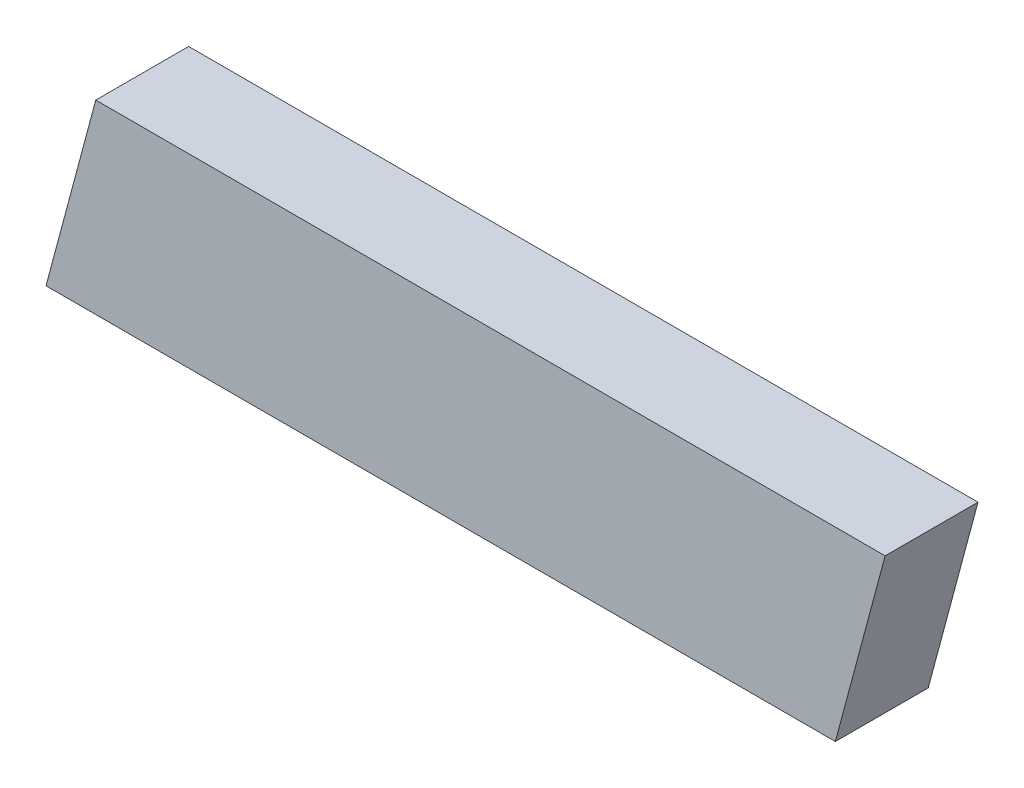
SolidWorks part; units mm, degrees
ref_plane "Front Plane" through (0, 0, 0) normal (0, 0, 1) x (1, 0, 0)
ref_plane "Top Plane" through (0, 0, 0) normal (0, 1, 0) x (1, 0, 0)
ref_plane "Right Plane" through (0, 0, 0) normal (1, 0, 0) x (0, 0, -1)
sketch "Sketch1" plane through (0, 0, 0) normal (0, 0, 1) x (1, 0, 0)
  line L0 (0, 0) -> (27.2236, 101.6)
  line L1 (0, 0) -> (431.8, 0)
  line L3 (27.2236, 101.6) -> (459.0236, 101.6)
  line L5 (431.8, 0) -> (459.0236, 101.6)
  dimension "D1" = 431.8
extrude "Boss-Extrude1" add sketch "Sketch1" along normal blind 50.8
